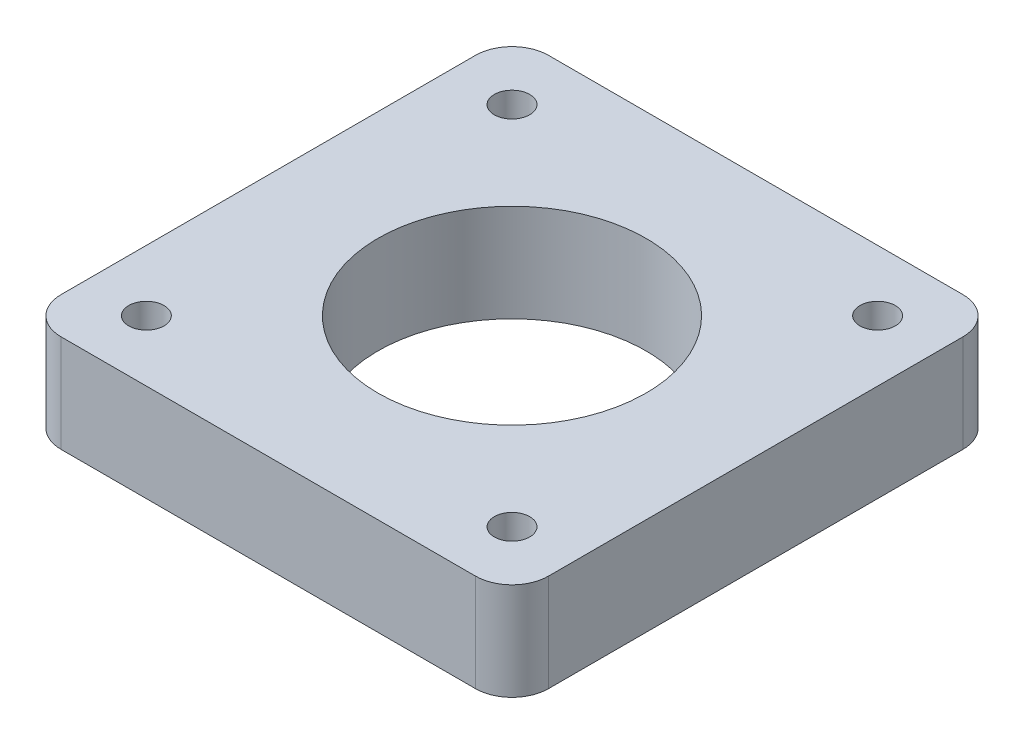
SolidWorks part; units mm, degrees
material "Oak"
ref_plane "Front Plane" through (0, 0, 0) normal (0, 0, 1) x (1, 0, 0)
ref_plane "Top Plane" through (0, 0, 0) normal (0, 1, 0) x (1, 0, 0)
ref_plane "Right Plane" through (0, 0, 0) normal (1, 0, 0) x (0, 0, -1)
sketch "Sketch1" plane through (0, 0, 0) normal (0, 1, 0) x (1, 0, 0)
  line L1 (0, 0.1114) -> (40, 0.1114)
  line L2 (0, 0.1114) -> (0, -39.8886)
  line L3 (0, -39.8886) -> (40, -39.8886)
  line L4 (40, 0.1114) -> (40, -39.8886)
  circle A0 centre (20, -19.8886) radius 11
  dimension "D5" = 22
  dimension "D1" = 40
  dimension "D2" = 40
  dimension "D3" = 20
  dimension "D4" = 20
extrude "Boss-Extrude1" add sketch "Sketch1" along normal blind 8
sketch "Sketch12" plane through (0, 8, 0) normal (0, 1, 0) x (1, 0, 0)
  line L0 (40, 0.1114) -> (0, 0.1114) construction
  line L1 (0, 0.1114) -> (0, -39.8886) construction
  line L2 (40, -39.8886) -> (40, 0.1114) construction
  line L3 (0, -39.8886) -> (40, -39.8886) construction
  circle A0 centre (5, -4.8886) radius 1.45
  circle A1 centre (35, -4.8886) radius 1.45
  circle A2 centre (35, -34.8886) radius 1.45
  circle A3 centre (5, -34.8886) radius 1.45
  dimension "D1" = 2.9
  dimension "D2" = 2.9
  dimension "D3" = 2.9
  dimension "D4" = 2.9
  dimension "D5" = 5
  dimension "D6" = 5
  dimension "D7" = 5
  dimension "D8" = 5
  dimension "D9" = 5
  dimension "D10" = 5
  dimension "D11" = 5
  dimension "D12" = 5
extrude "Cut-Extrude1" cut sketch "Sketch12" against normal through all
fillet "Fillet1" radius 3 4 edges at (40, 4, 39.8886) (40, 4, -0.1114) (0, 4, -0.1114) (0, 4, 39.8886)
